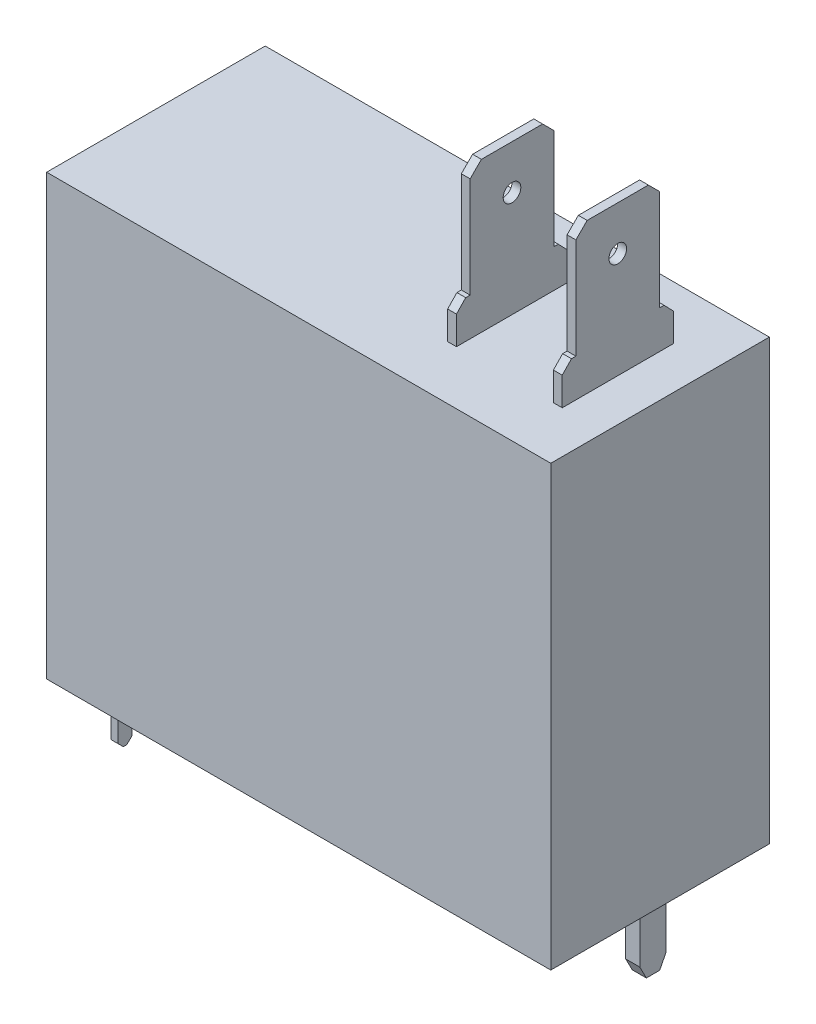
SolidWorks part; units mm, degrees
ref_plane "Alzado" through (0, 0, 0) normal (0, 0, 1) x (1, 0, 0)
ref_plane "Planta" through (0, 0, 0) normal (0, 1, 0) x (1, 0, 0)
ref_plane "Vista lateral" through (0, 0, 0) normal (1, 0, 0) x (0, 0, -1)
sketch "Croquis1" plane through (0, 0, 0) normal (0, 1, 0) x (1, 0, 0)
  line L1 (0, 0) -> (28.6, 0)
  line L2 (0, 0) -> (0, 12.4)
  line L3 (0, 12.4) -> (28.6, 12.4)
  line L4 (28.6, 0) -> (28.6, 12.4)
  dimension "D1" = 12.4
  dimension "D2" = 28.6
extrude "Saliente-Extruir1" add sketch "Croquis1" along normal blind 24.9
ref_plane "Plano1" through (25.95, 0, 0) normal (1, 0, 0) x (0, 0, -1)
sketch "Croquis2" plane through (25.95, 0, 0) normal (1, 0, 0) x (0, 0, -1)
  line L0 (6.2, 24.9) -> (6.2, 38.0828) construction
  line L1 (0, 24.9) -> (12.4, 24.9) construction
  line L2 (3.05, 24.9) -> (3.05, 26.5043)
  line L3 (3.05, 26.5043) -> (3.5733, 27.05)
  line L4 (3.5733, 27.05) -> (3.825, 27.05)
  line L5 (3.825, 27.05) -> (3.825, 32.762)
  line L6 (3.825, 32.762) -> (4.463, 33.4)
  line L7 (4.463, 33.4) -> (7.937, 33.4)
  line L8 (9.35, 24.9) -> (3.05, 24.9)
  line L9 (8.575, 32.762) -> (7.937, 33.4)
  line L10 (8.575, 27.05) -> (8.575, 32.762)
  line L11 (8.8267, 27.05) -> (8.575, 27.05)
  line L12 (9.35, 26.5043) -> (8.8267, 27.05)
  line L13 (9.35, 24.9) -> (9.35, 26.5043)
  circle A0 centre (6.2, 30.9) radius 0.5
  point P12 (6.2, 33.4)
  dimension "D5" = 1
  dimension "D1" = 6.35
  dimension "D2" = 2.375
  dimension "D3" = 8.5
  dimension "D4" = 45
  dimension "D6" = 2.5
  dimension "D7" = 6.3
extrude "Saliente-Extruir2" add sketch "Croquis2" along normal mid plane 0.5
ref_plane "Plano2" through (22.95, 0, 0) normal (1, 0, 0) x (0, 0, -1)
mirror "Simetría1" about plane through (22.95, 0, 0) normal (1, 0, 0) of "Saliente-Extruir2"
ref_plane "Plano3" through (27.8, 0, 0) normal (-1, 0, 0) x (0, 0, 1)
sketch "Croquis4" plane through (27.8, 0, 0) normal (-1, 0, 0) x (0, 0, 1)
  line L0 (-6.2, 0) -> (-6.2, -7) construction
  line L1 (-12.4, 0) -> (0, 0) construction
  line L2 (-6.95, 0) -> (-6.95, -2.7774)
  line L3 (-6.95, -2.7774) -> (-6.5775, -3.5)
  line L4 (-6.5775, -3.5) -> (-5.8225, -3.5)
  line L5 (-5.45, 0) -> (-6.95, 0)
  line L6 (-5.45, -2.7774) -> (-5.8225, -3.5)
  line L7 (-5.45, 0) -> (-5.45, -2.7774)
  point P6 (-6.95, -2.848)
  point P9 (-6.2, -3.37)
  point P10 (-6.8193, -3.2098)
  point P11 (-6.95, -3.3028)
  point P12 (-6.95, -2.7774)
  point P13 (-6.5775, -3.5)
  point P15 (-6.2, -3.5)
  dimension "D1" = 0.75
  dimension "D2" = 3.5
extrude "Saliente-Extruir3" add sketch "Croquis4" along normal mid plane 0.8
ref_plane "Plano4" through (1.8, 0, 0) normal (-1, 0, 0) x (0, 0, 1)
sketch "Croquis6" plane through (1.8, 0, 0) normal (-1, 0, 0) x (0, 0, 1)
  line L0 (-10.35, 0) -> (-10.35, -3.2004)
  line L1 (-12.4, 0) -> (0, 0) construction
  line L2 (-10.35, -3.2004) -> (-10.0504, -3.5)
  line L3 (-10.0504, -3.5) -> (-9.8496, -3.5)
  line L4 (-9.8496, -3.5) -> (-9.55, -3.2004)
  line L5 (-9.55, -3.2004) -> (-9.55, 0)
  line L6 (-9.55, 0) -> (-10.35, 0)
  line L7 (-9.95, 0) -> (-9.95, -4.6926) construction
  line L8 (-6.2, 0) -> (-6.2, -8.2135) construction
  line L9 (-2.85, 0) -> (-2.05, 0)
  line L10 (-2.85, -3.2004) -> (-2.85, 0)
  line L11 (-2.5504, -3.5) -> (-2.85, -3.2004)
  line L12 (-2.3496, -3.5) -> (-2.5504, -3.5)
  line L13 (-2.05, -3.2004) -> (-2.3496, -3.5)
  line L14 (-2.05, 0) -> (-2.05, -3.2004)
  point P10 (0, 0)
  point P13 (0, 0)
  point P14 (0, 0)
  dimension "D1" = 0.8
  dimension "D2" = 3.5
  dimension "D3" = 3.75
extrude "Saliente-Extruir4" add sketch "Croquis6" along normal mid plane 0.4
